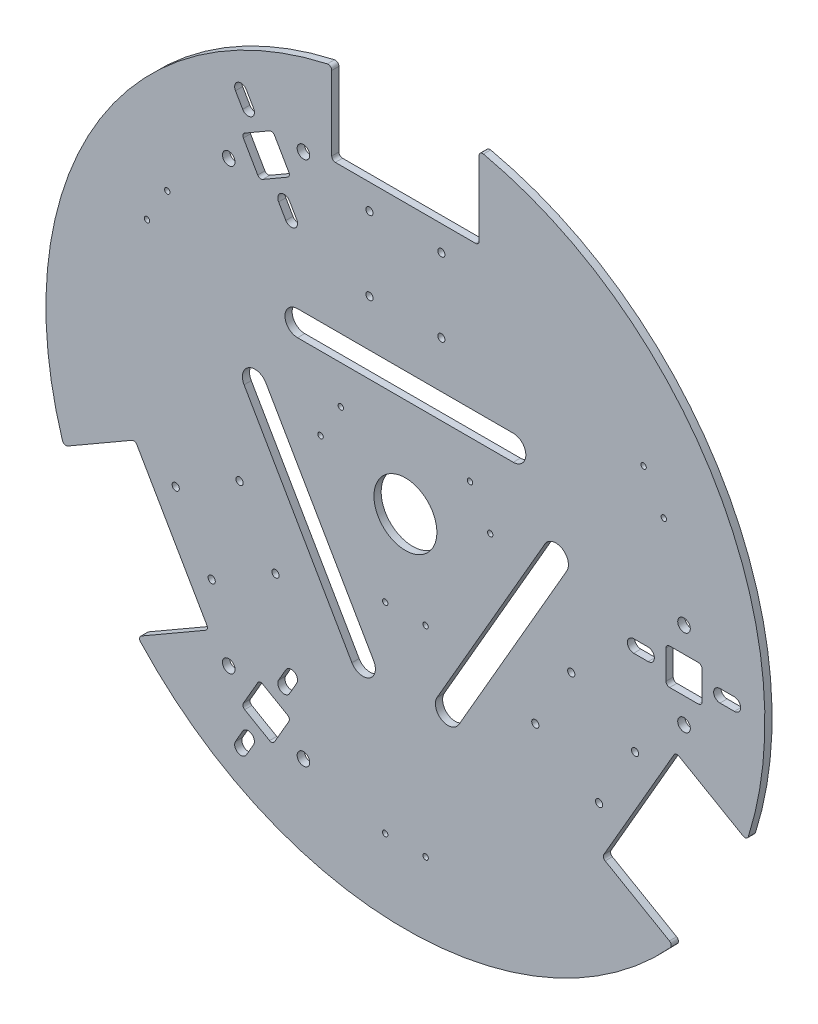
SolidWorks part; units mm, degrees
material "1060 Alloy"
ref_plane "Front Plane" through (0, 0, 0) normal (0, 0, 1) x (1, 0, 0)
ref_plane "Top Plane" through (0, 0, 0) normal (0, 1, 0) x (1, 0, 0)
ref_plane "Right Plane" through (0, 0, 0) normal (1, 0, 0) x (0, 0, -1)
sketch "Sketch1" plane through (0, 0, 0) normal (0, 0, 1) x (1, 0, 0)
  line L0 (0, 0) -> (-173.2051, 100) construction
  line L1 (0, 0) -> (173.2051, 100) construction
  line L2 (0, 0) -> (0, -200) construction
  line L3 (0, 0) -> (0, 200) construction
  circle A0 centre (0, 0) radius 200
  dimension "D1" = 400
  dimension "D2" = 120
  dimension "D3" = 120
extrude "Boss-Extrude2" add sketch "Sketch1" along normal blind 4
sketch "Sketch3" plane through (0, 0, 0) normal (0, 0, 1) x (1, 0, 0)
  line L0 (0, 0) -> (0, 200) construction
  line L3 (-41, 195.7524) -> (-41, 150)
  line L4 (-41, 150) -> (41, 150)
  line L5 (41, 195.7524) -> (41, 150)
  circle A0 centre (0, 0) radius 200 construction
  arc A1 (41, 195.7524) -> (-41, 195.7524) centre (0, 0) ccw
  dimension "D1" = 82
  dimension "D2" = 50
extrude "Cut-Extrude3" cut sketch "Sketch3" along normal up to surface (4 mm away) up to face at (200, 0, 4)
sketch "Sketch4" plane through (0, 0, 0) normal (0, 0, 1) x (1, 0, 0)
  circle A0 centre (0, 0) radius 17.5
  dimension "D1" = 35
extrude "Cut-Extrude4" cut sketch "Sketch4" along normal up to surface (4 mm away) up to face at (0, 73.9381, 4)
sketch "Sketch5" plane through (0, 0, 0) normal (0, 0, 1) x (1, 0, 0)
  line L0 (0, 0) -> (0, 200) construction
  circle A0 centre (-20, 136) radius 2
  circle A1 centre (-20, 95) radius 2
  circle A2 centre (20, 136) radius 2
  circle A3 centre (20, 95) radius 2
  dimension "D5" = 4
  dimension "D6" = 4
  dimension "D7" = 4
  dimension "D8" = 4
  dimension "D1" = 95
  dimension "D2" = 40
  dimension "D3" = 40
  dimension "D4" = 41
extrude "Cut-Extrude5" cut sketch "Sketch5" along normal up to surface (4 mm away) up to face at (17.5, 0, 4)
sketch "Sketch6" plane through (0, 0, 0) normal (0, 0, 1) x (1, 0, 0)
  line L0 (0, 0) -> (-199.1858, 115) construction
  line L1 (-132.5061, 89.4928) -> (-143.7561, 70.0072) construction
  line L2 (0, 0) -> (0, 171.0511) construction
  line L3 (-35.9442, 33.7428) -> (-47.1942, 14.2572) construction
  circle A1 centre (-143.7561, 70.0072) radius 1.5
  circle A2 centre (-132.5061, 89.4928) radius 1.5
  circle A3 centre (-35.9442, 33.7428) radius 1.5
  circle A4 centre (-47.1942, 14.2572) radius 1.5
  dimension "D1" = 3
  dimension "D2" = 3
  dimension "D3" = 3
  dimension "D4" = 3
  dimension "D8" = 48
  dimension "D5" = 22.5
  dimension "D6" = 22.5
  dimension "D7" = 111.5
  dimension "D9" = 60
extrude "Cut-Extrude6" cut sketch "Sketch6" along normal up to surface (4 mm away) up to face at (-18, 95, 4)
pattern_circular "CirPattern2" count 3 over 360 about axis through (0, 0, 0) along (0, 0, 1) of "Cut-Extrude6"
pattern_circular "CirPattern3" count 3 over 360 about axis through (0, 0, 0) along (0, 0, 1) of "Cut-Extrude5"
sketch "Sketch8" plane through (0, 0, 0) normal (0, 0, 1) x (1, 0, 0)
  line L0 (0, 0) -> (0, 200) construction
  line L2 (-60, 62) -> (60, 62) construction
  line L3 (-60, 69) -> (60, 69)
  line L4 (-60, 55) -> (60, 55)
  arc A0 (-60, 69) -> (-60, 55) centre (-60, 62) ccw
  arc A1 (60, 55) -> (60, 69) centre (60, 62) ccw
  point P7 (0, 62)
  point P22 (0, 55)
  dimension "D1" = 7
  dimension "D2" = 120
  dimension "D3" = 55
extrude "Cut-Extrude7" cut sketch "Sketch8" along normal up to surface (4 mm away) up to face at (129.7795, -50.6795, 4)
pattern_circular "CirPattern4" count 3 over 360 about axis through (0, 0, 0) along (0, 0, 1) of "Cut-Extrude7"
sketch "Sketch9" plane through (0, 0, 4) normal (0, 0, 1) x (1, 0, 0)
  line L0 (0, 0) -> (0, 200) construction
  line L2 (0, 0) -> (-115, 199.1858) construction
  line L3 (-91.1603, 137.8942) -> (-81.1603, 120.5737)
  line L4 (-73.8397, 147.8942) -> (-63.8397, 130.5737)
  line L5 (-91.1603, 137.8942) -> (-73.8397, 147.8942)
  line L6 (-81.1603, 120.5737) -> (-63.8397, 130.5737)
  line L7 (-86.1603, 129.2339) -> (-68.8397, 139.2339) construction
  line L8 (-67.5, 116.9134) -> (-63.5, 109.9852) construction
  line L9 (-64.4689, 118.6634) -> (-60.4689, 111.7352)
  line L10 (-70.5311, 115.1634) -> (-66.5311, 108.2352)
  line L11 (-87.5, 151.5544) -> (-91.5, 158.4826) construction
  line L12 (-84.4689, 153.3044) -> (-88.4689, 160.2326)
  line L13 (-90.5311, 149.8044) -> (-94.5311, 156.7326)
  circle A2 centre (-56.7154, 146.2339) radius 3.5
  arc A3 (-64.4689, 118.6634) -> (-70.5311, 115.1634) centre (-67.5, 116.9134) ccw
  arc A4 (-66.5311, 108.2352) -> (-60.4689, 111.7352) centre (-63.5, 109.9852) ccw
  circle A5 centre (-98.2846, 122.2339) radius 3.5
  arc A6 (-84.4689, 153.3044) -> (-90.5311, 149.8044) centre (-87.5, 151.5544) cw
  arc A7 (-94.5311, 156.7326) -> (-88.4689, 160.2326) centre (-91.5, 158.4826) cw
  point P19 (-65.5, 113.4493)
  point P28 (-89.5, 155.0185)
  dimension "D3" = 7
  dimension "D1" = 30
  dimension "D2" = 20
  dimension "D4" = 20
  dimension "D5" = 145
  dimension "D6" = 14
  dimension "D7" = 10
  dimension "D8" = 7
  dimension "D9" = 10
  dimension "D10" = 8
extrude "Cut-Extrude8" cut sketch "Sketch9" against normal up to surface (4 mm away) up to face at (-53.6936, -31, 0)
pattern_circular "CirPattern6" count 3 over 360 about axis through (0, 0, 0) along (0, 0, 1) of "Cut-Extrude3"
fillet "Fillet1" radius 2 12 edges at (149.0265, -133.3832, 2) (109.4038, -110.507, 2) (190.0265, -62.3692, 2) (150.4038, -39.493, 2) (-109.4038, -110.507, 2) (-149.0265, -133.3832, 2) (-150.4038, -39.493, 2) (-190.0265, -62.3692, 2) (41, 150, 2) (41, 195.7524, 2) (-41, 150, 2) (-41, 195.7524, 2)
fillet "Fillet2" radius 2 4 edges at (-63.8397, 130.5737, 2) (-81.1603, 120.5737, 2) (-91.1603, 137.8942, 2) (-73.8397, 147.8942, 2)
pattern_circular "CirPattern7" count 3 over 360 about axis through (0, 0, 0) along (0, 0, 1) of "Cut-Extrude8", "Fillet2"
